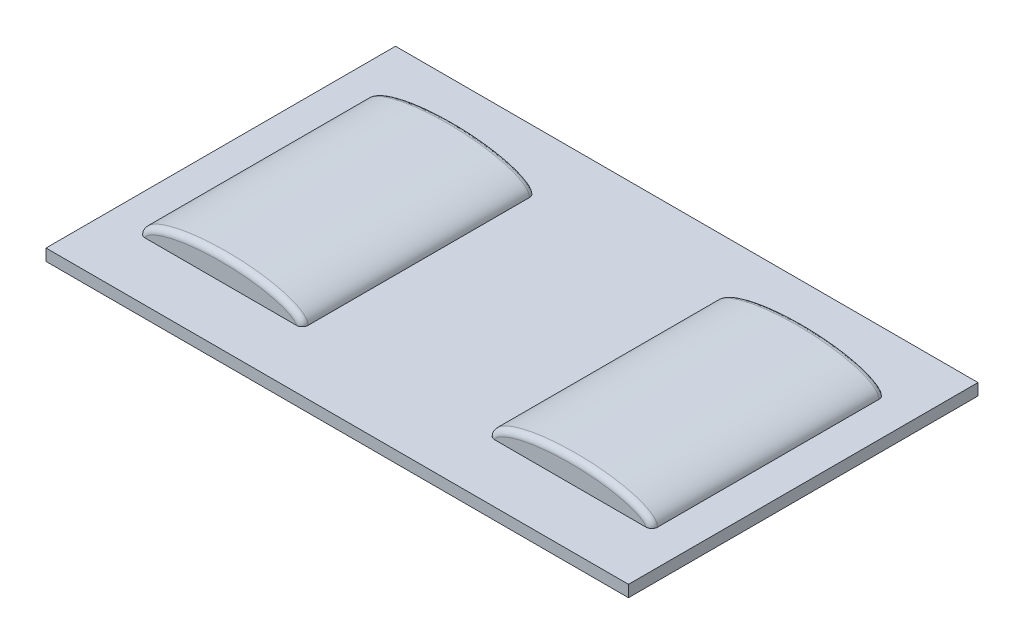
SolidWorks part; units mm, degrees
ref_plane "Спереди" through (0, 0, 0) normal (0, 0, 1) x (1, 0, 0)
ref_plane "Сверху" through (0, 0, 0) normal (0, 1, 0) x (1, 0, 0)
ref_plane "Справа" through (0, 0, 0) normal (1, 0, 0) x (0, 0, -1)
other "Configuration Table"
sketch "Эскиз1" plane through (0, 0, 0) normal (0, 1, 0) x (1, 0, 0)
  line L1 (-25, -15) -> (25, -15)
  line L2 (-25, -15) -> (-25, 15)
  line L3 (-25, 15) -> (25, 15)
  line L4 (25, -15) -> (25, 15)
  line L5 (-25, -15) -> (25, 15) construction
  line L6 (-25, 15) -> (25, -15) construction
  point P0 (0, 0)
  dimension "D1" = 50
  dimension "D2" = 30
extrude "Бобышка-Вытянуть1" add sketch "Эскиз1" along normal blind 1
sketch "Эскиз2" plane through (0, 0, 0) normal (0, 0, 1) x (1, 0, 0)
  line L0 (-25, 1) -> (25, 1) construction
  line L1 (-22, 1) -> (-8, 1)
  line L2 (-25, 1) -> (-22, 1) construction
  line L3 (0, -1000) -> (0, 49000) construction
  line L4 (-8, 1) -> (0, 1) construction
  line L5 (8, 1) -> (22, 1)
  line L6 (0, 1) -> (8, 1) construction
  line L7 (22, 1) -> (25, 1) construction
  ellipse E0 centre (-15, 1) end of major axis (-8, 1) minor radius 2 (-8, 1) -> (-22, 1) ccw
  ellipse E1 centre (-15, 1) end of major axis (-8, 1) minor radius 2 (-22, 1) -> (-8, 1) ccw construction
  ellipse E2 centre (15, 1) end of major axis (8, 1) minor radius 2 (8, 1) -> (22, 1) cw
  dimension "D2" = 2
  dimension "D1" = 15
  dimension "D3" = 7
extrude "Бобышка-Вытянуть2" add sketch "Эскиз2" along normal mid plane 20
fillet "Скругление2" radius 0.5 4 edges at (15, 3, 10) (15, 3, -10) (-15, 3, -10) (-15, 3, 10)
